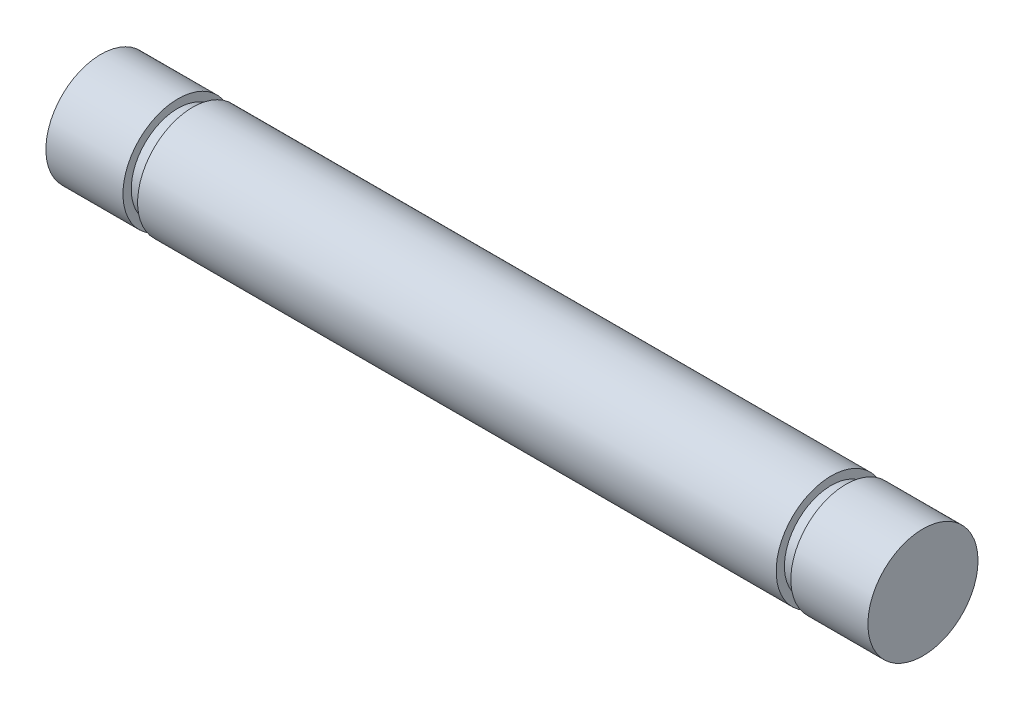
SolidWorks part; units mm, degrees
ref_plane "Alzado" through (0, 0, 0) normal (1, 0, 0) x (0, 1, 0)
ref_plane "Planta" through (0, 0, 0) normal (0, 0, 1) x (0, 1, 0)
ref_plane "Vista lateral" through (0, 0, 0) normal (0, 1, 0) x (-1, 0, 0)
sketch "Croquis1" plane through (0, 0, 0) normal (0, 1, 0) x (-1, 0, 0)
  line L1 (-17.4, 3) -> (17.4, 3)
  line L6 (22.4, 3) -> (22.4, 0)
  line L7 (-22.4, 0) -> (22.4, 0) construction
  line L22 (-22.4, 0) -> (22.4, 0)
  line L23 (17.4, 3) -> (17.4, 2.55)
  line L24 (17.4, 2.55) -> (18.2, 2.55)
  line L25 (18.2, 2.55) -> (18.2, 3)
  line L26 (18.2, 3) -> (22.4, 3)
  line L27 (0, 0) -> (0, 3) construction
  line L28 (-18.2, 3) -> (-22.4, 3)
  line L29 (-18.2, 2.55) -> (-18.2, 3)
  line L30 (-17.4, 2.55) -> (-18.2, 2.55)
  line L31 (-17.4, 3) -> (-17.4, 2.55)
  line L32 (-22.4, 3) -> (-22.4, 0)
  dimension "D1" = 5
  dimension "D2" = 6
  dimension "D3" = 34.8
  dimension "D5" = 0.8
  dimension "D7" = 0.45
revolve "Revolución1" add sketch "Croquis1" angle 360 about L7
equation "\"ancho_circlip\"=0.8"
equation "\"ranura_circlip\"=0.45"
